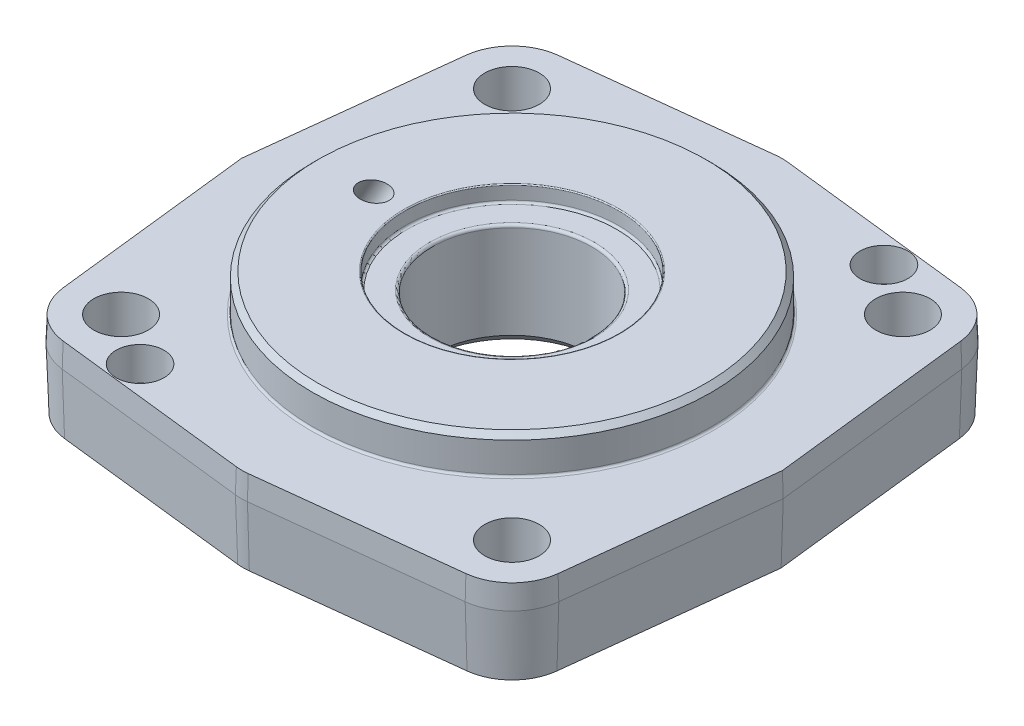
SolidWorks part; units mm, degrees
material "2P Cast Iron"
ref_plane "Front Plane" through (0, 0, 0) normal (0, 0, 1) x (1, 0, 0)
ref_plane "Top Plane" through (0, 0, 0) normal (0, 1, 0) x (1, 0, 0)
ref_plane "Right Plane" through (0, 0, 0) normal (1, 0, 0) x (0, 0, -1)
sketch "Sketch2" plane through (0, 0, 0) normal (0, 1, 0) x (1, 0, 0)
  line L0 (1.1316, 50.8711) -> (37.8816, 46.6858)
  line L1 (-1.1316, 50.8711) -> (-37.8816, 46.6858)
  line L2 (0, -55.2489) -> (0, 70.268) construction
  line L3 (-46.6858, 37.8816) -> (-51, 0)
  line L4 (-51, 0) -> (-46.6858, -37.8816)
  line L5 (-77.9612, 0) -> (67.3997, 0) construction
  line L6 (1.1316, -50.8711) -> (37.8816, -46.6858)
  line L7 (-1.1316, -50.8711) -> (-37.8816, -46.6858)
  line L8 (51, 0) -> (46.6858, -37.8816)
  line L9 (46.6858, 37.8816) -> (51, 0)
  arc A0 (-46.6858, -37.8816) -> (-37.8816, -46.6858) centre (-36.75, -36.75) ccw
  arc A1 (37.8816, -46.6858) -> (46.6858, -37.8816) centre (36.75, -36.75) ccw
  arc A2 (37.8816, 46.6858) -> (46.6858, 37.8816) centre (36.75, 36.75) cw
  arc A3 (-37.8816, 46.6858) -> (-46.6858, 37.8816) centre (-36.75, 36.75) ccw
  arc A4 (1.1316, -50.8711) -> (-1.1316, -50.8711) centre (0, -40.9354) cw
  arc A5 (1.1316, 50.8711) -> (-1.1316, 50.8711) centre (0, 40.9354) ccw
  point P15 (-45.7856, -45.7856)
  point P18 (45.7856, -45.7856)
  point P21 (45.7856, 45.7856)
  point P24 (-45.7856, 45.7856)
  point P27 (0, -51)
  point P30 (0, 51)
  dimension "D4" = 10
  dimension "D5" = 10
  dimension "D1" = 73.5
  dimension "D2" = 73.5
  dimension "D3" = 102
  dimension "D6" = 102
extrude "Boss-Extrude1" add sketch "Sketch2" along normal mid plane 23 draft 2
sketch "Sketch5" plane through (0, -11.5, 0) normal (0, -1, 0) x (1, 0, 0)
  line L0 (0, -27.936) -> (0, 32.288) construction
  line L1 (-31.053, 0) -> (30.6187, 0) construction
  circle A0 centre (-36.75, 36.75) radius 5.125
  circle A1 centre (36.75, 36.75) radius 5.125
  circle A2 centre (-36.75, -36.75) radius 5.125
  circle A3 centre (36.75, -36.75) radius 5.125
  arc A6 (-37.8361, 46.2868) -> (-46.2868, 37.8361) centre (-36.75, 36.75) ccw construction
  dimension "D1" = 10.25
extrude "Cut-Extrude3" cut sketch "Sketch5" against normal through all
sketch "Sketch4" plane through (0, -11.5, 0) normal (0, -1, 0) x (1, 0, 0)
  circle A0 centre (0, 0) radius 44
  circle A1 centre (0, 0) radius 41.375
  dimension "D1" = 82.75
  dimension "D2" = 88
extrude "Cut-Extrude2" cut sketch "Sketch4" against normal blind 1.75
sketch "Sketch6" plane through (0, 0, 0) normal (1, 0, 0) x (0, 0, -1)
  line L0 (37.45, 10.5) -> (37.45, 4.9)
  line L2 (37.85, 4.5) -> (75, 4.5)
  line L3 (20.1, 8.9) -> (20.1, 11.3)
  line L4 (20.3, 11.5) -> (36.45, 11.5)
  line L5 (36.45, 11.5) -> (37.45, 10.5)
  line L6 (75, 4.5) -> (75, 13.5)
  line L7 (75, 13.5) -> (0, 13.5)
  line L8 (19.7, 8.5) -> (15.5, 8.5)
  line L9 (15, 8) -> (15, -9.5)
  line L10 (0, -11.5) -> (37.8361, -11.5) construction
  line L11 (17, -11.5) -> (0, -11.5)
  line L13 (0, 29.1961) -> (0, -17.807) construction
  line L14 (0, -11.5) -> (0, 13.5)
  line L15 (15, -9.5) -> (17, -11.5)
  arc A0 (20.1, 11.3) -> (20.3, 11.5) centre (20.3, 11.3) cw
  arc A1 (37.85, 4.5) -> (37.45, 4.9) centre (37.85, 4.9) cw
  arc A2 (15.5, 8.5) -> (15, 8) centre (15.5, 8) ccw
  arc A5 (20.1, 8.9) -> (19.7, 8.5) centre (19.7, 8.9) cw
  point P9 (20.1, 11.5)
  dimension "D10" = 2
  dimension "D11" = 0.4
  dimension "D12" = 0.5
  dimension "D13" = 3
  dimension "D14" = 0.4
  dimension "D8" = 0.2
  dimension "D2" = 16
  dimension "D3" = 40.2
  dimension "D4" = 1
  dimension "D5" = 30
  dimension "D6" = 74.9
  dimension "D7" = 45
  dimension "D9" = 150
  dimension "D15" = 2
  dimension "D16" = 45
revolve "Cut-Revolve1" cut sketch "Sketch6" angle 360 about L13
sketch "Sketch9" plane through (0, 0, 0) normal (0, 0, 1) x (1, 0, 0)
  line L0 (-39.5, -11.5) -> (-24.1076, 14.7241) construction
  line L2 (-39.5, -11.5) -> (-37.344, -12.7655) construction
  line L3 (-37.344, -12.7655) -> (-23.844, 10.2345)
  line L4 (-23.844, 10.2345) -> (-26, 11.5) construction
  line L5 (0, 0) -> (0, -39.6581) construction
  line L6 (20.3, 11.5) -> (-20.3, 11.5) construction
  line L7 (-37.344, -12.7655) -> (-41.3936, -19.6648)
  line L8 (-41.3936, -19.6648) -> (-43.5496, -18.3993)
  line L9 (-24.5027, 14.0509) -> (-22.3467, 12.7854)
  line L10 (-23.844, 10.2345) -> (-22.3467, 12.7854)
  line L11 (-43.5496, -18.3993) -> (-24.5027, 14.0509)
  line L12 (-46.2868, -11.5) -> (-37.8361, -11.5) construction
  dimension "D1" = 26
  dimension "D2" = 8
  dimension "D3" = 39.5
  dimension "D4" = 5
  dimension "D5" = 29.6271
revolve "Cut-Revolve2" cut sketch "Sketch9" angle 360 about L11
sketch "Sketch11" plane through (0, 4.5, 0) normal (0, 1, 0) x (1, 0, 0)
  line L0 (26.8934, 43.0384) -> (0, 0) construction
  line L1 (0, 0) -> (-72.2669, 0) construction
  line L2 (0, 0) -> (0, 56.7744) construction
  circle A0 centre (0, 0) radius 50.75 construction
  point P3 (26.8934, 43.0384)
  point P4 (-26.8934, -43.0384)
  dimension "D1" = 101.5
  dimension "D2" = 32
hole_wizard "CBORE for M5 Hex Socket Head Cap Screw1" positions "Sketch13" profile "Sketch12" counterbore size "M5" standard "ISO" end condition through all
sketch "Sketch13" plane through (0, 4.5, 0) normal (0, 1, 0) x (1, 0, 0)
  point P0 (26.8934, 43.0384)
  point P3 (-26.8934, -43.0384)
sketch "Sketch12" plane through (26.8934, 4.5, -43.0384) normal (1, 0, 0) x (0, 0, 1)
  line L0 (0, 0) -> (0, 16)
  line L1 (2.75, 15.975) -> (2.775, 16)
  line L2 (2.75, 15.975) -> (2.75, 6.325)
  line L3 (2.75, 6.325) -> (2.775, 6.3)
  line L4 (2.775, 6.3) -> (4.5, 6.3)
  line L5 (4.5, 6.3) -> (4.5, 0)
  line L7 (4.5, 0) -> (0, 0)
  line L9 (-2.75, 6.325) -> (-2.775, 6.3) construction
  line L11 (0, -6.35) -> (0, 107.95) construction
  line L12 (2.775, 16) -> (0, 16)
  line L13 (-2.75, 15.975) -> (-2.775, 16) construction
  dimension "Thru Hole Dia." = 5.5
  dimension "Thru Hole Depth" = 16
  dimension "C'Bore Dia." = 9
  dimension "C'Bore Depth" = 6.3
  dimension "Mid C'Sink Dia." = 5.55
  dimension "Mid C'Sink Angle" = 90
  dimension "Far C'Sink Dia." = 5.55
  dimension "Far C'Sink Angle" = 90
